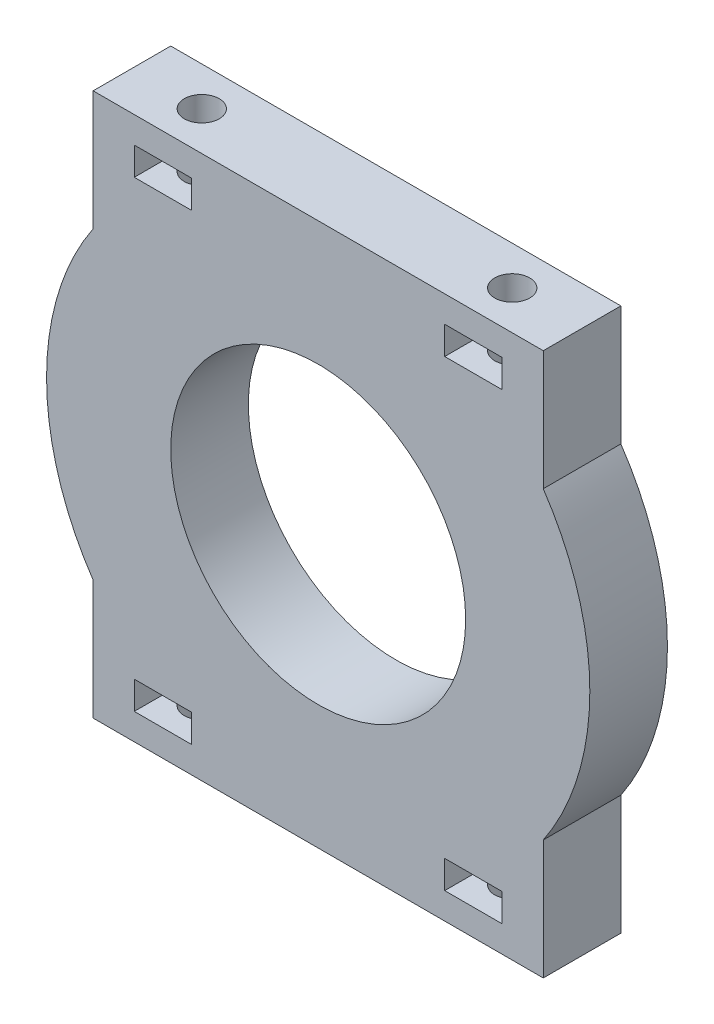
SolidWorks part; units mm, degrees
material "ABS"
ref_plane "Alzado" through (0, 0, 0) normal (0, 0, 1) x (1, 0, 0)
ref_plane "Planta" through (0, 0, 0) normal (0, 1, 0) x (1, 0, 0)
ref_plane "Vista lateral" through (0, 0, 0) normal (1, 0, 0) x (0, 0, -1)
sketch "Croquis1" plane through (0, 0, 0) normal (0, 0, 1) x (1, 0, 0)
  line L0 (-29, 19.5959) -> (-29, 35)
  line L1 (-29, -35) -> (29, -35)
  line L2 (-29, -35) -> (-29, -19.5959)
  line L3 (-29, 35) -> (29, 35)
  line L4 (29, -35) -> (29, -19.5959)
  line L5 (-29, -35) -> (29, 35) construction
  line L6 (-29, 35) -> (29, -35) construction
  line L7 (29, 19.5959) -> (29, 35)
  arc A0 (-29, 19.5959) -> (-29, -19.5959) centre (0, 0) ccw
  arc A1 (29, -19.5959) -> (29, 19.5959) centre (0, 0) ccw
  circle A2 centre (0, 0) radius 19
  dimension "D1" = 70
  dimension "D4" = 38
  dimension "D2" = 58
  dimension "D3" = 70
extrude "Saliente-Extruir1" add sketch "Croquis1" along normal mid plane 10
ref_plane "Plano1" through (0, 28, 0) normal (0, 1, 0) x (1, 0, 0)
sketch "Croquis5" plane through (0, 28, 0) normal (0, 1, 0) x (1, 0, 0)
  line L0 (20, 0) -> (-20, 0) construction
  line L1 (-23.7, -2.1362) -> (-23.7, -5)
  line L2 (-23.7, 2.1362) -> (-23.7, -2.1362)
  line L3 (-23.7, -2.1362) -> (-20, -4.2724) construction
  line L4 (-20, -4.2724) -> (-16.3, -2.1362) construction
  line L5 (-16.3, -2.1362) -> (-16.3, 2.1362)
  line L6 (-16.3, 2.1362) -> (-20, 4.2724)
  line L7 (-20, 4.2724) -> (-23.7, 2.1362)
  line L8 (16.3, 2.1362) -> (16.3, -2.1362)
  line L9 (16.3, -2.1362) -> (20, -4.2724) construction
  line L10 (20, -4.2724) -> (23.7, -2.1362) construction
  line L11 (23.7, -2.1362) -> (23.7, 2.1362)
  line L12 (23.7, 2.1362) -> (20, 4.2724)
  line L13 (20, 4.2724) -> (16.3, 2.1362)
  line L14 (29, -5) -> (-29, -5) construction
  line L15 (-23.7, -5) -> (-16.3, -5)
  line L16 (-16.3, -5) -> (-16.3, -2.1362)
  line L17 (16.3, -2.1362) -> (16.3, -5)
  line L18 (16.3, -5) -> (23.7, -5)
  line L19 (23.7, -5) -> (23.7, -2.1362)
  circle A0 centre (-20, 0) radius 3.7 construction
  circle A1 centre (20, 0) radius 3.7 construction
  point P4 (0, 0)
  dimension "D1" = 7.4
  dimension "D2" = 40
extrude "Cortar-Extruir1" cut sketch "Croquis5" along normal blind 3.6
sketch "Croquis6" plane through (0, 35, 0) normal (0, 1, 0) x (1, 0, 0)
  line L0 (0, 0) -> (-16.3, 0) construction
  line L1 (-16.3, -5) -> (-16.3, 2.1362) construction
  line L2 (-16.3, 0) -> (-23.7, 0) construction
  line L3 (-23.7, 2.1362) -> (-23.7, -5) construction
  line L4 (0, -5.5) -> (0, 5.5) construction
  circle A0 centre (-20, 0) radius 2.25
  circle A1 centre (20, 0) radius 2.25
  dimension "D1" = 4.5
extrude "Cortar-Extruir2" cut sketch "Croquis6" against normal blind 10
mirror "Simetría1" about plane through (0, 0, 0) normal (0, 1, 0) of "Cortar-Extruir2", "Cortar-Extruir1"
